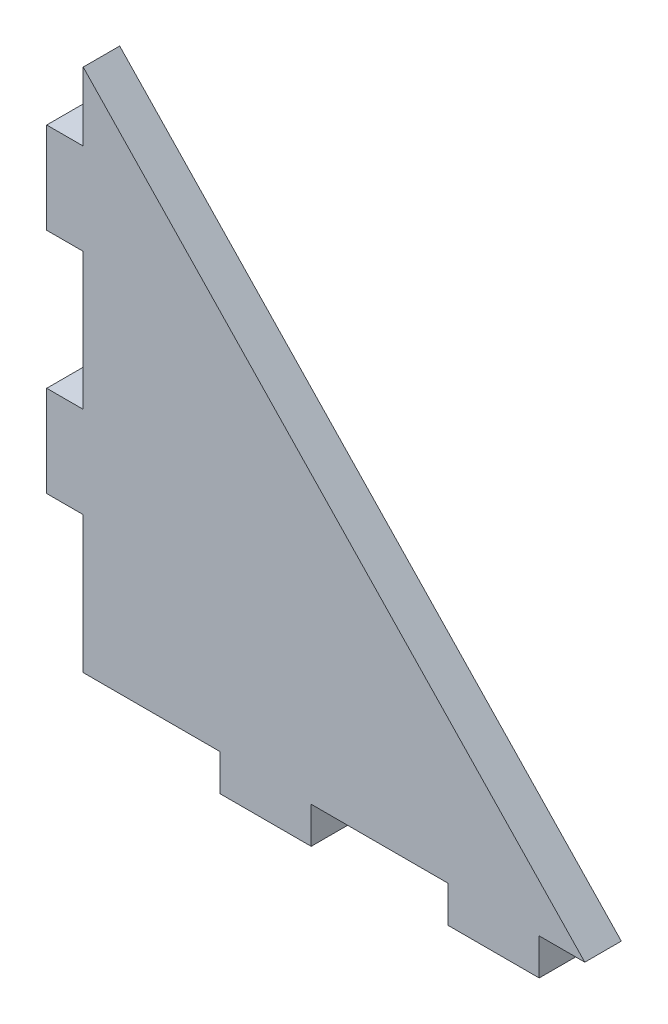
SolidWorks part; units mm, degrees
ref_plane "Plan de face" through (0, 0, 0) normal (0, 0, 1) x (1, 0, 0)
ref_plane "Plan de dessus" through (0, 0, 0) normal (0, 1, 0) x (1, 0, 0)
ref_plane "Plan de droite" through (0, 0, 0) normal (1, 0, 0) x (0, 0, -1)
sketch "Esquisse1" plane through (0, 0, 0) normal (0, 0, 1) x (1, 0, 0)
  line L0 (0, 0) -> (110, 0)
  line L1 (0, 0) -> (0, 115)
  line L2 (0, 115) -> (110, 0)
  dimension "D1" = 115
  dimension "D2" = 110
extrude "Boss.-Extru.1" add sketch "Esquisse1" along normal blind 8
sketch "Esquisse2" plane through (0, 0, 0) normal (0, 0, 1) x (1, 0, 0)
  line L0 (0, 115) -> (0, 0) construction
  line L1 (0, 30) -> (-8, 30)
  line L2 (0, 30) -> (0, 50)
  line L3 (0, 50) -> (-8, 50)
  line L4 (-8, 30) -> (-8, 50)
  line L5 (0, 80) -> (0, 100)
  line L6 (0, 80) -> (-8, 80)
  line L7 (-8, 80) -> (-8, 100)
  line L8 (0, 100) -> (-8, 100)
  dimension "D1" = 30
  dimension "D2" = 20
  dimension "D3" = 8
  dimension "D4" = 2
extrude "Boss.-Extru.2" add sketch "Esquisse2" along normal blind 8
sketch "Esquisse3" plane through (0, 0, 0) normal (0, 0, 1) x (1, 0, 0)
  line L0 (0, 0) -> (110, 0) construction
  line L1 (30, 0) -> (50, 0)
  line L2 (30, 0) -> (30, -8)
  line L3 (30, -8) -> (50, -8)
  line L4 (50, 0) -> (50, -8)
  line L5 (80, 0) -> (80, -8)
  line L6 (80, 0) -> (100, 0)
  line L7 (100, 0) -> (100, -8)
  line L8 (80, -8) -> (100, -8)
  dimension "D1" = 30
  dimension "D2" = 20
  dimension "D3" = 8
  dimension "D4" = 2
extrude "Boss.-Extru.3" add sketch "Esquisse3" along normal blind 8
